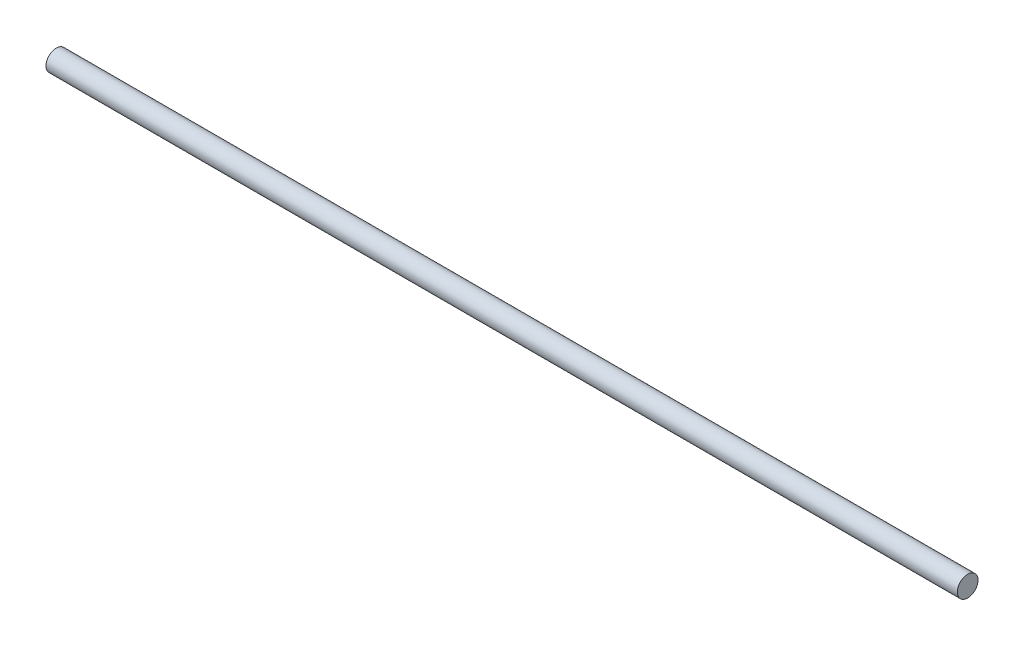
SolidWorks part; units mm, degrees
material "AISI 4340 Steel, normalized"
ref_plane "Front Plane" through (0, 0, 0) normal (0, 0, 1) x (1, 0, 0)
ref_plane "Top Plane" through (0, 0, 0) normal (0, 1, 0) x (1, 0, 0)
ref_plane "Right Plane" through (0, 0, 0) normal (1, 0, 0) x (0, 0, -1)
sketch "Sketch4" plane through (0, 0, 0) normal (0, 0, 1) x (1, 0, 0)
  line L0 (0, 0) -> (140, 0)
  dimension "D1" = 140
sketch "Sketch5" plane through (0, 0, 0) normal (1, 0, 0) x (0, 0, -1)
  circle A0 centre (0, 0) radius 1.5875
  dimension "D1" = 3.175
sweep "Sweep1" add profiles "Sketch5" path "Sketch4"
